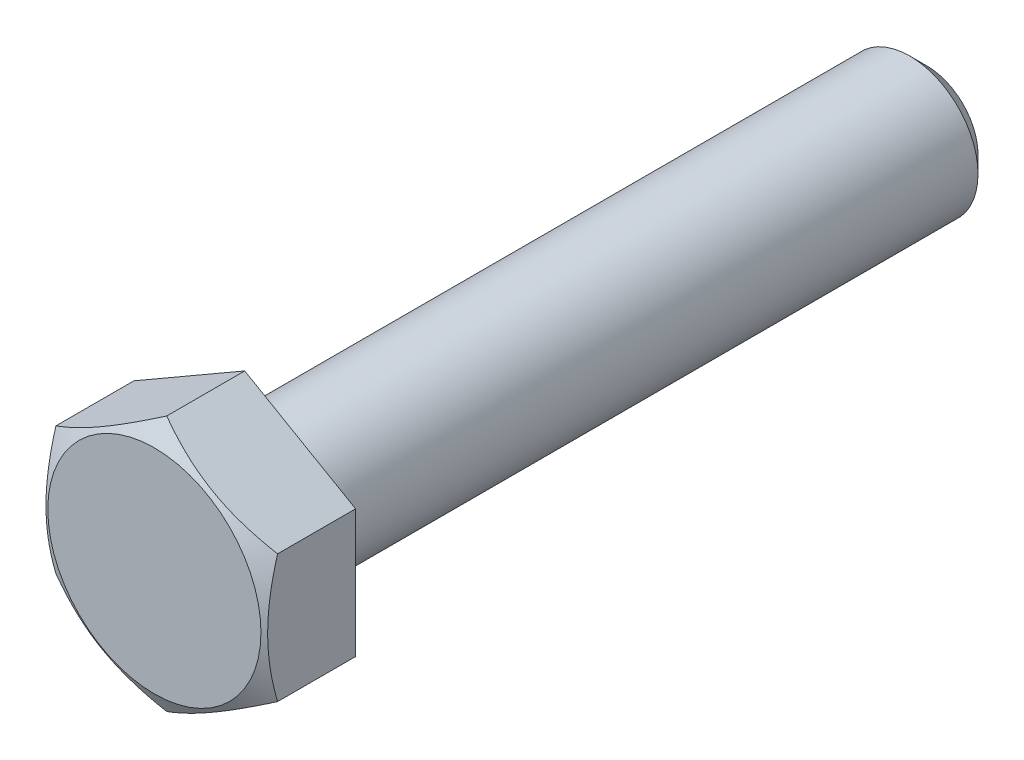
SolidWorks part; units mm, degrees
material "Простая углеродистая сталь"
ref_plane "Спереди" through (0, 0, 0) normal (0, 0, 1) x (1, 0, 0)
ref_plane "Сверху" through (0, 0, 0) normal (0, 1, 0) x (1, 0, 0)
ref_plane "Справа" through (0, 0, 0) normal (1, 0, 0) x (0, 0, -1)
sketch "Эскиз1" plane through (0, 0, 0) normal (0, 0, 1) x (1, 0, 0)
  line L1 (0, 7.5056) -> (-6.5, 3.7528)
  line L2 (-6.5, 3.7528) -> (-6.5, -3.7528)
  line L3 (-6.5, -3.7528) -> (0, -7.5056)
  line L4 (0, -7.5056) -> (6.5, -3.7528)
  line L5 (6.5, -3.7528) -> (6.5, 3.7528)
  line L6 (6.5, 3.7528) -> (0, 7.5056)
  circle A0 centre (0, 0) radius 6.5 construction
  dimension "S" = 13
extrude "Бобышка-Вытянуть1" add sketch "Эскиз1" along normal blind 5.3
sketch "Эскиз2" plane through (0, 0, 5.3) normal (0, 0, 1) x (1, 0, 0)
  circle A0 centre (0, 0) radius 6.25
  dimension "D1" = 12.5
extrude "Вырез-Вытянуть1" cut sketch "Эскиз2" against normal through all draft 60 flip side to cut
sketch "Эскиз3" plane through (0, 0, 0) normal (0, 0, -1) x (-1, 0, 0)
  circle A0 centre (0, 0) radius 4
  dimension "d" = 8
extrude "Бобышка-Вытянуть2" add sketch "Эскиз3" along normal blind 40
cosmetic thread "Условное изображение резьбы1" parameters "D1"=22, "D2"=6.619
chamfer "Фаска1" distance 1 angle 45 1 edges at (-4, 0, -40)
fillet "Скругление1" radius 0.5 1 edges at (4, 0, 0)
